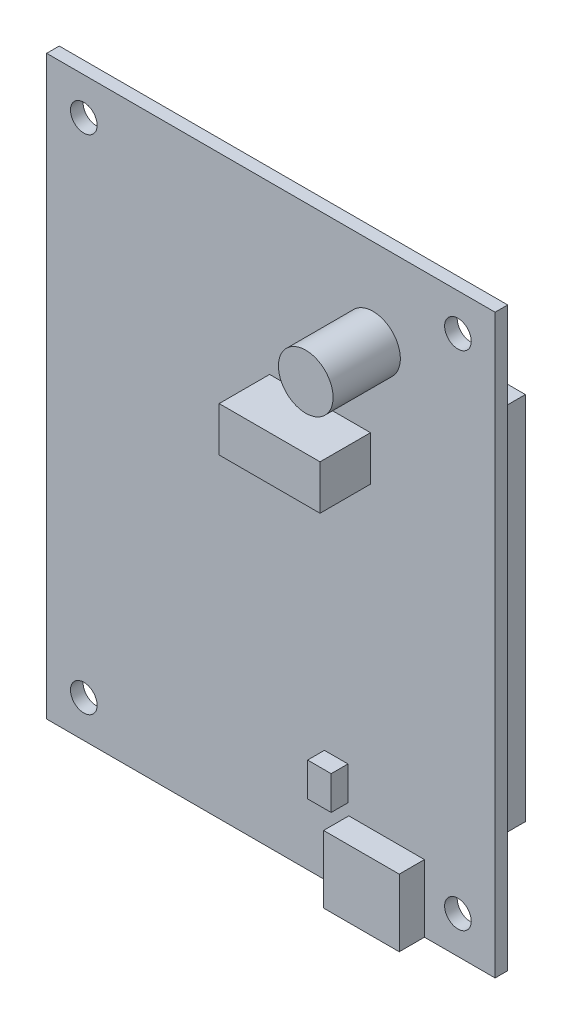
SolidWorks part; units mm, degrees
ref_plane "前视基准面" through (0, 0, 0) normal (0, 0, 1) x (1, 0, 0)
ref_plane "上视基准面" through (0, 0, 0) normal (0, 1, 0) x (1, 0, 0)
ref_plane "右视基准面" through (0, 0, 0) normal (1, 0, 0) x (0, 0, -1)
sketch "草图1" plane through (0, 0, 0) normal (0, 0, 1) x (1, 0, 0)
  line L0 (0, 4.42) -> (53.34, 4.42) construction
  line L1 (0, 0) -> (53.34, 0)
  line L2 (0, 0) -> (0, 68.58)
  line L3 (0, 68.58) -> (53.34, 68.58)
  line L4 (53.34, 0) -> (53.34, 68.58)
  line L5 (0, 64.16) -> (53.34, 64.16) construction
  line L6 (4.42, 68.58) -> (4.42, 0) construction
  line L7 (48.92, 68.58) -> (48.92, 0) construction
  circle A0 centre (48.92, 64.16) radius 1.585
  circle A1 centre (4.42, 64.16) radius 1.585
  circle A2 centre (4.42, 4.42) radius 1.585
  circle A3 centre (48.92, 4.42) radius 1.585
  point P21 (0, 0)
  point P22 (0, 0)
  point P23 (0, 0)
  point P24 (0, 0)
  point P25 (0, 0)
  dimension "D7" = 3.17
  dimension "D8" = 3.17
  dimension "D9" = 3.17
  dimension "D10" = 3.17
  dimension "D1" = 68.58
  dimension "D2" = 53.34
  dimension "D3" = 4.42
  dimension "D4" = 4.42
  dimension "D5" = 4.42
  dimension "D6" = 4.42
extrude "凸台-拉伸1" add sketch "草图1" along normal blind 1.5
sketch "草图2" plane through (0, 0, 1.5) normal (0, 0, 1) x (1, 0, 0)
  circle A0 centre (38.82, 58.16) radius 3.25
  circle A2 centre (48.92, 64.16) radius 1.585 construction
  dimension "D3" = 6.5
  dimension "D1" = 10.1
  dimension "D2" = 6
extrude "凸台-拉伸2" add sketch "草图2" along normal blind 8
sketch "草图3" plane through (0, 0, 1.5) normal (0, 0, 1) x (1, 0, 0)
  line L1 (38.52, 48.76) -> (26.52, 48.76)
  line L2 (38.52, 48.76) -> (38.52, 43.46)
  line L3 (38.52, 43.46) -> (26.52, 43.46)
  line L4 (26.52, 48.76) -> (26.52, 43.46)
  circle A0 centre (48.92, 64.16) radius 1.585 construction
  dimension "D1" = 10.4
  dimension "D2" = 15.4
  dimension "D3" = 12
  dimension "D4" = 5.3
extrude "凸台-拉伸3" add sketch "草图3" along normal blind 6
sketch "草图4" plane through (0, 0, 1.5) normal (0, 0, 1) x (1, 0, 0)
  line L0 (53.34, 0) -> (53.34, 68.58) construction
  line L1 (33.04, 13.3) -> (35.84, 13.3)
  line L2 (33.04, 13.3) -> (33.04, 9.3)
  line L3 (33.04, 9.3) -> (35.84, 9.3)
  line L4 (35.84, 13.3) -> (35.84, 9.3)
  line L5 (0, 0) -> (53.34, 0) construction
  dimension "D1" = 17.5
  dimension "D2" = 9.3
  dimension "D3" = 4
  dimension "D4" = 2.8
extrude "凸台-拉伸4" add sketch "草图4" along normal blind 2
sketch "草图5" plane through (0, 0, 0) normal (0, 0, -1) x (-1, 0, 0)
  line L0 (-53.34, 0) -> (-53.34, 68.58) construction
  line L1 (-46.64, 56.4) -> (-51.44, 56.4)
  line L2 (-46.64, 56.4) -> (-46.64, 12.4)
  line L3 (-46.64, 12.4) -> (-51.44, 12.4)
  line L4 (-51.44, 56.4) -> (-51.44, 12.4)
  line L5 (-1.9, 56.4) -> (-6.7, 56.4)
  line L6 (-1.9, 56.4) -> (-1.9, 12.4)
  line L7 (-1.9, 12.4) -> (-6.7, 12.4)
  line L8 (-6.7, 56.4) -> (-6.7, 12.4)
  line L9 (0, 0) -> (-53.34, 0) construction
  line L10 (0, 68.58) -> (0, 0) construction
  dimension "D1" = 4.8
  dimension "D2" = 4.8
  dimension "D3" = 44
  dimension "44" = 44
  dimension "D4" = 1.9
  dimension "D5" = 12.4
  dimension "D6" = 12.4
  dimension "D7" = 1.9
extrude "凸台-拉伸5" add sketch "草图5" along normal blind 4
sketch "草图6" plane through (0, 0, 1.5) normal (0, 0, 1) x (1, 0, 0)
  line L0 (0, 0) -> (53.34, 0) construction
  line L1 (35.94, 0) -> (44.94, 0)
  line L2 (35.94, 0) -> (35.94, 8)
  line L3 (35.94, 8) -> (44.94, 8)
  line L4 (44.94, 0) -> (44.94, 8)
  line L5 (53.34, 0) -> (53.34, 68.58) construction
  dimension "D1" = 8.4
  dimension "D2" = 8
  dimension "D3" = 9
extrude "凸台-拉伸6" add sketch "草图6" along normal blind 3
